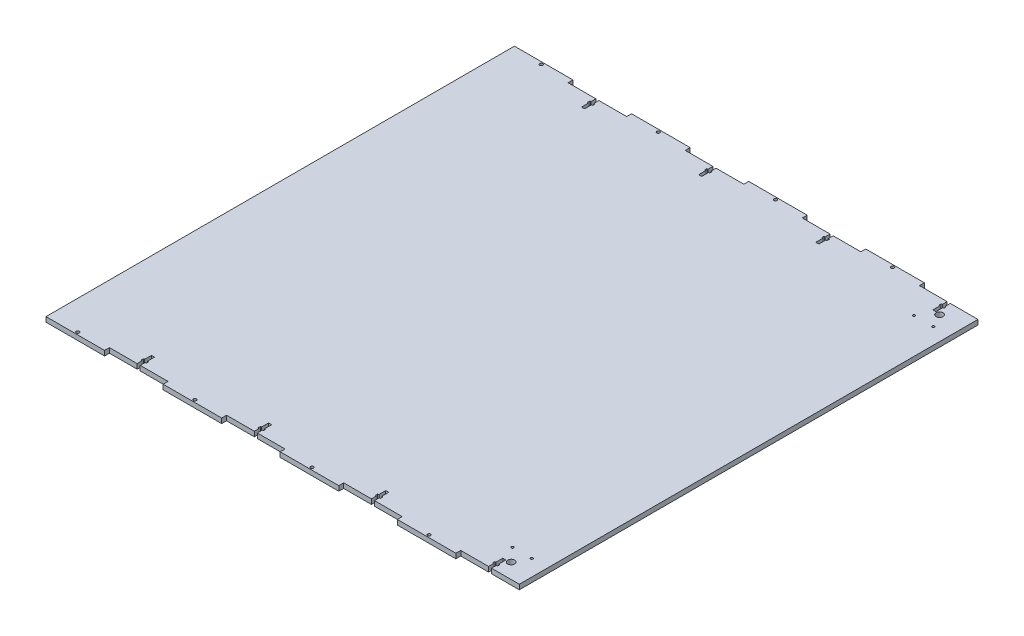
SolidWorks part; units mm, degrees
material "Acrylic (Medium-high impact)"
ref_plane "Front Plane" through (0, 0, 0) normal (0, 0, 1) x (1, 0, 0)
ref_plane "Top Plane" through (0, 0, 0) normal (0, 1, 0) x (1, 0, 0)
ref_plane "Right Plane" through (0, 0, 0) normal (1, 0, 0) x (0, 0, -1)
sketch "Sketch1" plane through (0, 0, 0) normal (0, 1, 0) x (1, 0, 0)
  line L0 (-304.8, 0) -> (304.8, 0)
  line L1 (-304.8, -304.8) -> (304.8, -304.8)
  line L2 (-304.8, -304.8) -> (-304.8, 304.8)
  line L3 (-304.8, 304.8) -> (304.8, 304.8)
  line L4 (304.8, -304.8) -> (304.8, 304.8)
  line L5 (-304.8, -304.8) -> (304.8, 304.8) construction
  line L6 (-304.8, 304.8) -> (304.8, -304.8) construction
  point P0 (0, 0)
  dimension "D1" = 609.6
  dimension "D2" = 609.6
extrude "Boss-Extrude1" add sketch "Sketch1" along normal mid plane 6.35 contours L1 L4 L0 L2
sketch "Sketch2" plane through (0, 3.175, 0) normal (0, 1, 0) x (1, 0, 0)
  line L2 (304.8, -304.8) -> (304.8, 0) construction
  line L10 (-228.6, -304.8) -> (-152.4, -304.8)
  line L11 (-228.6, -304.8) -> (-228.6, -298.45)
  line L12 (-228.6, -298.45) -> (-152.4, -298.45)
  line L13 (-152.4, -304.8) -> (-152.4, -298.45)
  line L14 (-304.8, -304.8) -> (304.8, -304.8) construction
  line L15 (-76.2, -304.8) -> (0, -304.8)
  line L16 (-76.2, -304.8) -> (-76.2, -298.45)
  line L17 (-76.2, -298.45) -> (0, -298.45)
  line L18 (0, -304.8) -> (0, -298.45)
  line L19 (-304.8, -304.8) -> (-304.8, 0) construction
  line L20 (76.2, -304.8) -> (152.4, -304.8)
  line L21 (76.2, -304.8) -> (76.2, -298.45)
  line L22 (76.2, -298.45) -> (152.4, -298.45)
  line L23 (152.4, -304.8) -> (152.4, -298.45)
  line L24 (228.6, -304.8) -> (304.8, -304.8)
  line L25 (228.6, -304.8) -> (228.6, -298.45)
  line L26 (228.6, -298.45) -> (304.8, -298.45)
  line L27 (304.8, -304.8) -> (304.8, -298.45)
  line L28 (-192.5, -298.45) -> (-192.5, -292.05)
  line L29 (-192.5, -292.05) -> (-193.89, -292.05)
  line L30 (-193.89, -292.05) -> (-193.89, -288.85)
  line L31 (-193.89, -288.85) -> (-192.5, -288.85)
  line L32 (-192.5, -288.85) -> (-192.5, -279.8)
  line L33 (-192.5, -279.8) -> (-188.5, -279.8)
  line L34 (-188.5, -279.8) -> (-188.5, -288.85)
  line L35 (-188.5, -288.85) -> (-187.11, -288.85)
  line L36 (-187.11, -288.85) -> (-187.11, -292.05)
  line L37 (-187.11, -292.05) -> (-188.5, -292.05)
  line L38 (-188.5, -292.05) -> (-188.5, -298.45)
  line L39 (-190.5, -279.8) -> (-190.5, -298.45) construction
  line L40 (-40.1, -292.05) -> (-41.49, -292.05)
  line L41 (-41.49, -292.05) -> (-41.49, -288.85)
  line L42 (-41.49, -288.85) -> (-40.1, -288.85)
  line L43 (-40.1, -288.85) -> (-40.1, -279.8)
  line L44 (-40.1, -279.8) -> (-36.1, -279.8)
  line L45 (-36.1, -279.8) -> (-36.1, -288.85)
  line L46 (-36.1, -288.85) -> (-34.71, -288.85)
  line L47 (-34.71, -288.85) -> (-34.71, -292.05)
  line L48 (-34.71, -292.05) -> (-36.1, -292.05)
  line L49 (-40.1, -298.45) -> (-40.1, -292.05)
  line L50 (-36.1, -292.05) -> (-36.1, -298.45)
  line L51 (-38.1, -279.8) -> (-38.1, -298.45) construction
  line L52 (112.3, -292.05) -> (110.91, -292.05)
  line L53 (110.91, -292.05) -> (110.91, -288.85)
  line L54 (110.91, -288.85) -> (112.3, -288.85)
  line L55 (112.3, -288.85) -> (112.3, -279.8)
  line L56 (112.3, -279.8) -> (116.3, -279.8)
  line L57 (116.3, -279.8) -> (116.3, -288.85)
  line L58 (116.3, -288.85) -> (117.69, -288.85)
  line L59 (117.69, -288.85) -> (117.69, -292.05)
  line L60 (117.69, -292.05) -> (116.3, -292.05)
  line L61 (112.3, -298.45) -> (112.3, -292.05)
  line L62 (116.3, -292.05) -> (116.3, -298.45)
  line L63 (114.3, -279.8) -> (114.3, -298.45) construction
  line L64 (264.7, -292.05) -> (263.31, -292.05)
  line L65 (263.31, -292.05) -> (263.31, -288.85)
  line L66 (263.31, -288.85) -> (264.7, -288.85)
  line L67 (264.7, -288.85) -> (264.7, -279.8)
  line L68 (264.7, -279.8) -> (268.7, -279.8)
  line L69 (268.7, -279.8) -> (268.7, -288.85)
  line L70 (268.7, -288.85) -> (270.09, -288.85)
  line L71 (270.09, -288.85) -> (270.09, -292.05)
  line L72 (270.09, -292.05) -> (268.7, -292.05)
  line L73 (264.7, -298.45) -> (264.7, -292.05)
  line L74 (268.7, -292.05) -> (268.7, -298.45)
  line L75 (266.7, -279.8) -> (266.7, -298.45) construction
  line L76 (304.8, -304.8) -> (304.8, 0) construction
  circle A0 centre (-266.7, -301.625) radius 2
  circle A1 centre (-114.3, -301.625) radius 2
  circle A2 centre (38.1, -301.625) radius 2
  circle A3 centre (190.5, -301.625) radius 2
  circle A4 centre (274.46, -278.775) radius 4.5
  circle A5 centre (283.8, -261.3) radius 1.5
  circle A6 centre (258.8, -261.3) radius 1.5
  point P22 (-76.2, -301.625)
  line M22 (-304.8, -304.8) -> (304.8, -304.8)
  line M23 (304.8, -304.8) -> (304.8, 0)
  dimension "D10" = 4
  dimension "D19" = 9
  dimension "D22" = 21
  dimension "D24" = 3
  dimension "D25" = 3
  dimension "D1" = 76.2
  dimension "D2" = 76.2
  dimension "D3" = 76.2
  dimension "D4" = 76.2
  dimension "D5" = 76.2
  dimension "D6" = 76.2
  dimension "D7" = 76.2
  dimension "D8" = 6.35
  dimension "D9" = 76.2
  dimension "D11" = 3.175
  dimension "D12" = 38.1
  dimension "D13" = 4
  dimension "D14" = 6.78
  dimension "D15" = 3.2
  dimension "D16" = 6.4
  dimension "D17" = 18.65
  dimension "D18" = 38.1
  dimension "D20" = 19.675
  dimension "D21" = 30.34
  dimension "D23" = 43.5
  dimension "D26" = 46
extrude "Cut-Extrude1" cut sketch "Sketch2" along direction (0, 1, 0) on the side of the normal blind 2.54 and the other way blind 10 contours A0 | L13 L12 L11 M22 | L38 L37 L36 L35 L34 L33 L32 L31 L30 L29 L28 L12 | A1 | L18 L17 L16 M22 | L50 L48 L47 L46 L45 L44 L43 L42 L41 L40 L49 L17 | A2 | L23 L22 L21 M22 | L62 L60 L59 L58 L57 L56 L55 L54 L53 L52 L61 L22 | A3 | L26 L25 M22 M23 | L74 L72 L71 L70 L69 L68 L67 L66 L65 L64 L73 L26 | A4 | A5 | A6
mirror "Mirror1" about plane through (0, 3.175, 0) normal (0, 0, -1) of "Cut-Extrude1", "Boss-Extrude1"
